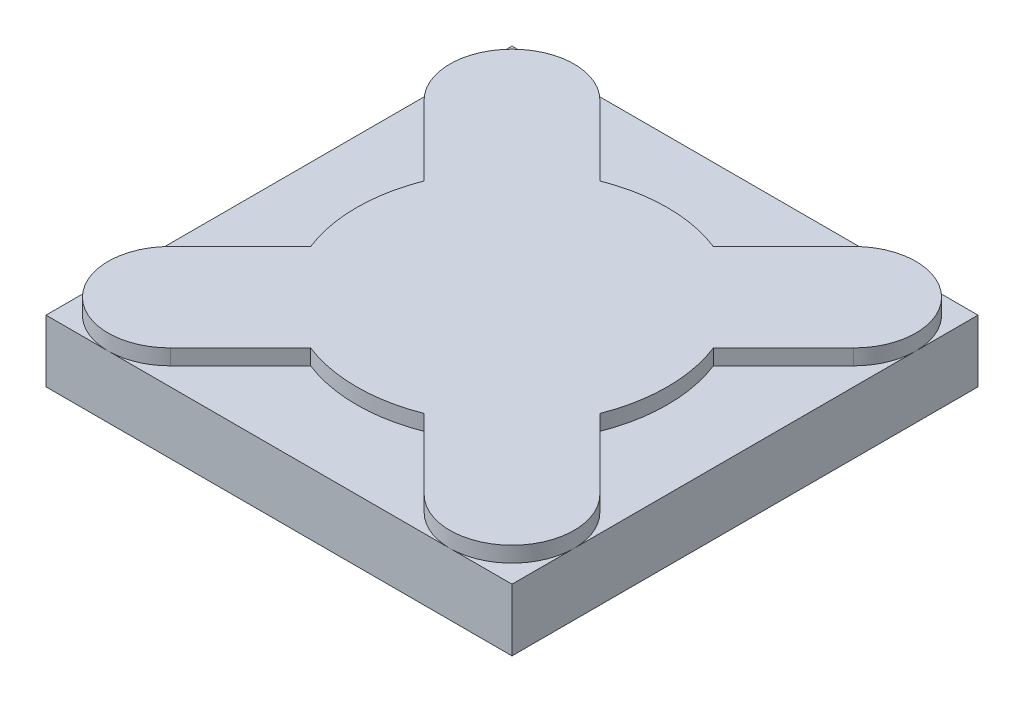
SolidWorks part; units mm, degrees
ref_plane "Front Plane" through (0, 0, 0) normal (0, 0, 1) x (1, 0, 0)
ref_plane "Top Plane" through (0, 0, 0) normal (0, 1, 0) x (1, 0, 0)
ref_plane "Right Plane" through (0, 0, 0) normal (1, 0, 0) x (0, 0, -1)
sketch "Sketch2" plane through (0, 0, 0) normal (0, 1, 0) x (1, 0, 0)
  line L0 (0, 0) -> (27.7426, 0) construction
  line L5 (-19.05, -19.05) -> (17.5621, 17.5621) construction
  line L6 (-19.05, 19.05) -> (17.5621, -17.5621) construction
  line L7 (-17.5621, 10.3779) -> (-11.8226, 4.6384)
  line L8 (-11.8226, -4.6384) -> (-17.5621, -10.3779)
  line L9 (-4.6384, -11.8226) -> (-10.3779, -17.5621)
  line L10 (-10.3779, 17.5621) -> (-4.6384, 11.8226)
  line L11 (0, 15.1549) -> (0, -12.723) construction
  line L12 (4.6384, -11.8226) -> (10.3779, -17.5621)
  line L13 (10.3779, 17.5621) -> (4.6384, 11.8226)
  line L14 (17.5621, 10.3779) -> (11.8226, 4.6384)
  line L15 (11.8226, -4.6384) -> (17.5621, -10.3779)
  arc A0 (-10.3779, 17.5621) -> (-17.5621, 10.3779) centre (-13.97, 13.97) ccw
  arc A1 (17.5621, -10.3779) -> (10.3779, -17.5621) centre (13.97, -13.97) cw
  arc A2 (-10.3779, -17.5621) -> (-17.5621, -10.3779) centre (-13.97, -13.97) cw
  arc A3 (17.5621, 10.3779) -> (10.3779, 17.5621) centre (13.97, 13.97) ccw
  arc A4 (-11.8226, 4.6384) -> (-11.8226, -4.6384) centre (0, 0) ccw
  arc A5 (-4.6384, -11.8226) -> (4.6384, -11.8226) centre (0, 0) ccw
  arc A6 (4.6384, 11.8226) -> (-4.6384, 11.8226) centre (0, 0) ccw
  arc A7 (11.8226, -4.6384) -> (11.8226, 4.6384) centre (0, 0) ccw
  point P0 (0, 0)
  point P23 (-6.1913, 11.0887)
  point P31 (-5.1248, 11.8226)
  point P32 (11.4028, 5.5916)
  point P33 (-3.7735, -12.1264)
  point P34 (11.8226, -4.6384)
  dimension "D2" = 10.16
  dimension "D3" = 25.4
  dimension "D1" = 27.94
ref_plane "Plane1" through (0, 0, 0) normal (0, 1, 0) x (1, 0, 0)
sketch "Sketch3" plane through (0, 0, 0) normal (0, 1, 0) x (1, 0, 0)
  line L1 (-19.05, -19.05) -> (19.05, -19.05)
  line L2 (-19.05, -19.05) -> (-19.05, 19.05)
  line L3 (-19.05, 19.05) -> (19.05, 19.05)
  line L4 (19.05, -19.05) -> (19.05, 19.05)
  line L5 (-19.05, -19.05) -> (19.05, 19.05) construction
  line L6 (-19.05, 19.05) -> (19.05, -19.05) construction
  point P0 (0, 0)
  dimension "D1" = 38.1
extrude "Boss-Extrude2" add sketch "Sketch3" against normal blind 5.08
extrude "Boss-Extrude3" add sketch "Sketch2" along normal blind 1.27
ref_plane "Plane2" through (0, 1.27, 0) normal (0, 1, 0) x (1, 0, 0)
